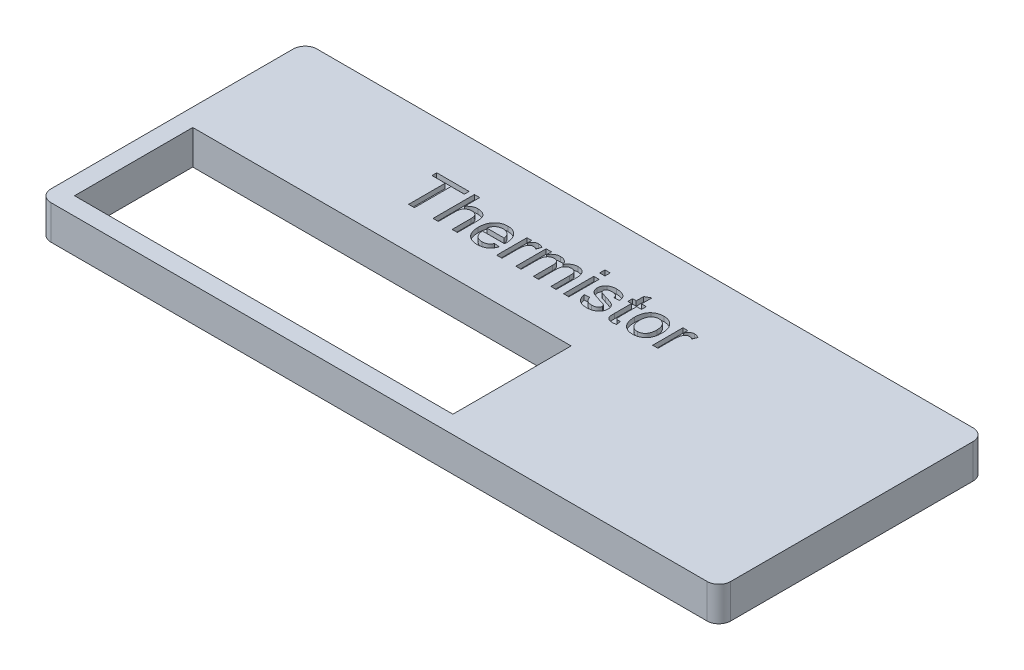
SolidWorks part; units mm, degrees
material "ABS"
ref_plane "Front Plane" through (0, 0, 0) normal (0, 0, 1) x (1, 0, 0)
ref_plane "Top Plane" through (0, 0, 0) normal (0, 1, 0) x (1, 0, 0)
ref_plane "Right Plane" through (0, 0, 0) normal (1, 0, 0) x (0, 0, -1)
sketch "Sketch1" plane through (0, 0, 0) normal (0, 1, 0) x (1, 0, 0)
  line L1 (1, 0) -> (56.5, 0)
  line L2 (0, 1) -> (0, 21.5)
  line L3 (1, 22.5) -> (56.5, 22.5)
  line L4 (57.5, 1) -> (57.5, 21.5)
  arc A0 (56.5, 22.5) -> (57.5, 21.5) centre (56.5, 21.5) cw
  arc A1 (57.5, 1) -> (56.5, 0) centre (56.5, 1) cw
  arc A2 (1, 0) -> (0, 1) centre (1, 1) cw
  arc A3 (0, 21.5) -> (1, 22.5) centre (1, 21.5) cw
  point P11 (0, 0)
  dimension "D1" = 1
extrude "Boss-Extrude1" add sketch "Sketch1" along normal blind 2.9
sketch "Sketch2" plane through (0, 0, 0) normal (0, 1, 0) x (1, 0, 0)
  line L0 (0, 0) -> (0, 1.5)
  line L1 (0, 21.5) -> (0, 1) construction
  line L2 (0, 1.5) -> (1.5, 1.5)
  line L3 (1.5, 1.5) -> (5.5, 1.5)
  line L8 (5.5, 1.5) -> (33.5, 1.5)
  line L9 (33.5, 1.5) -> (33.5, 11.5)
  line L10 (33.5, 11.5) -> (1.5, 11.5)
  line L12 (1.5, 11.5) -> (1.5, 1.5)
extrude "Cut-Extrude1" cut sketch "Sketch2" along normal blind 10
ref_plane "Plane1" through (0, 3, 0) normal (0, 1, 0) x (1, 0, 0)
sketch "Sketch3" plane through (0, 3, 0) normal (0, 1, 0) x (1, 0, 0)
  text T0 "Thermistor"
  point P1 (0, 0)
  point P2 (0, 0)
extrude "Cut-Extrude2" cut sketch "Sketch3" against normal blind 0.5
